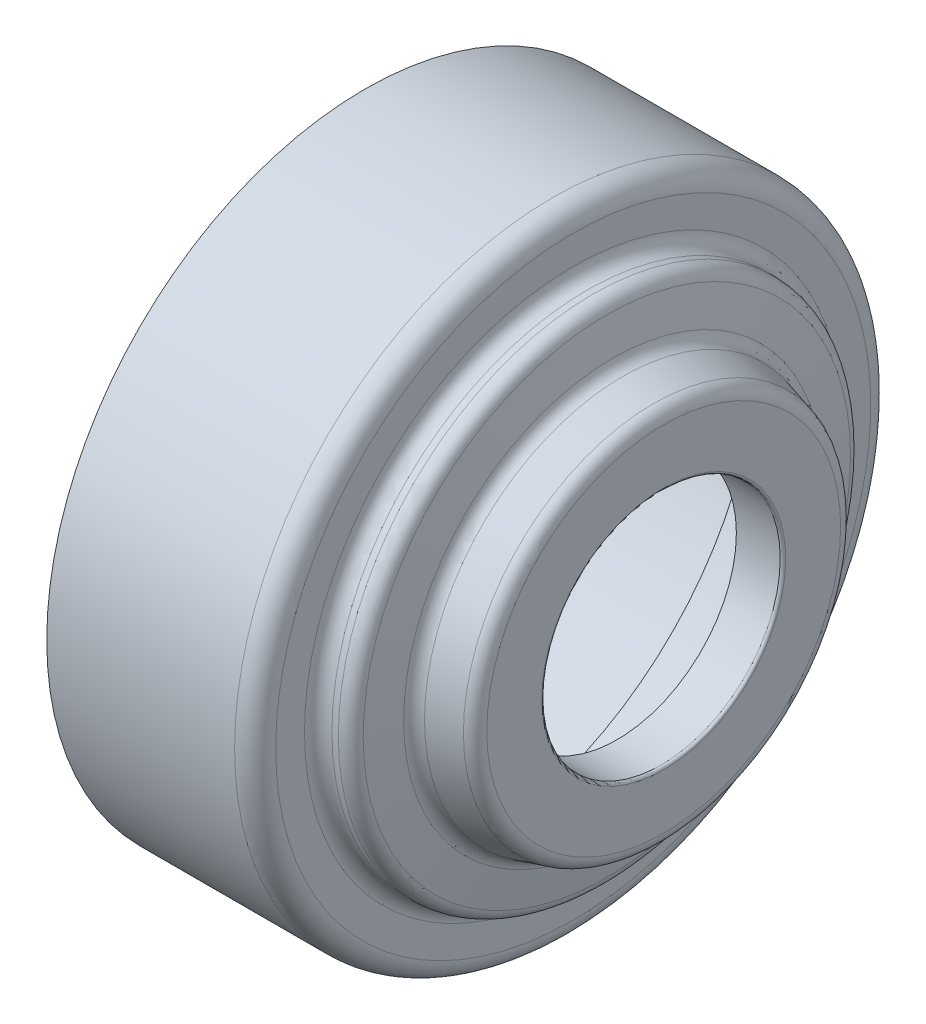
SolidWorks part; units mm, degrees
ref_plane "前视基准面" through (0, 0, 0) normal (0, 0, 1) x (1, 0, 0)
ref_plane "上视基准面" through (0, 0, 0) normal (0, 1, 0) x (1, 0, 0)
ref_plane "右视基准面" through (0, 0, 0) normal (1, 0, 0) x (0, 0, -1)
sketch "草图2" plane through (0, 0, 0) normal (0, 0, 1) x (1, 0, 0)
  line L0 (-36.9366, 0) -> (44.5849, 0) construction
  line L1 (0, 36.0368) -> (0, -37.1166) construction
  line L2 (-14, 22) -> (-6.9, 22)
  line L3 (-6.9, 22) -> (-6.9, 21.6)
  line L4 (-6.9, 21.6) -> (0, 21.6)
  line L5 (0, 21.6) -> (0, 17.4)
  line L6 (0, 17.4) -> (2.5, 17.4)
  line L9 (6.6, 12.75) -> (6.6, 9.4)
  line L10 (6.6, 9.4) -> (4.4, 9.4)
  line L11 (4.4, 9.4) -> (4.4, 8.7)
  line L12 (4.4, 8.7) -> (7.8, 8.7)
  line L13 (-14, 22) -> (-14, 23.2)
  line L14 (-14, 23.2) -> (1.2, 23.2)
  line L15 (1.2, 23.2) -> (1.2, 18.6)
  line L16 (1.2, 18.6) -> (3.5069, 18.6)
  line L19 (7.8, 13.6708) -> (7.8, 8.7)
  line L20 (2.5, 17.4) -> (3.1573, 13.6725)
  line L21 (3.5069, 18.6) -> (4.2063, 14.6337)
  line L22 (6.6, 12.75) -> (3.1573, 13.6725)
  line L23 (7.8, 13.6708) -> (4.2063, 14.6337)
  dimension "D1" = 44
  dimension "D2" = 0.4
  dimension "D3" = 7.1
  dimension "D4" = 14
  dimension "D5" = 34.8
  dimension "D6" = 2.5
  dimension "D7" = 18.8
  dimension "D8" = 0.7
  dimension "D9" = 4.4
  dimension "D10" = 2.2
  dimension "D11" = 25.5
  dimension "D12" = 46.4
  dimension "D13" = 1.6
  dimension "D14" = 1.2
  dimension "D15" = 10
  dimension "D16" = 105
  dimension "D17" = 1.2
  dimension "D18" = 1.2
  dimension "D19" = 1.2
  dimension "D20" = 1.2
  dimension "D21" = 1.2
revolve "旋转1" add sketch "草图2" angle 360 about L0
fillet "圆角1" radius 0.2 5 edges at (0, 0, 17.4) (0, 0, 21.6) (7.8, 0, 8.7) (2.5, 0, 17.4) (6.6, 0, 12.75)
fillet "圆角2" radius 1 4 edges at (1.2, 0, 18.6) (3.5069, 0, 18.6) (7.8, 0, 13.6708) (4.2063, 0, 14.6337)
fillet "圆角3" radius 1.5 2 edges at (1.2, 0, 23.2) (3.1573, 0, 13.6725)
